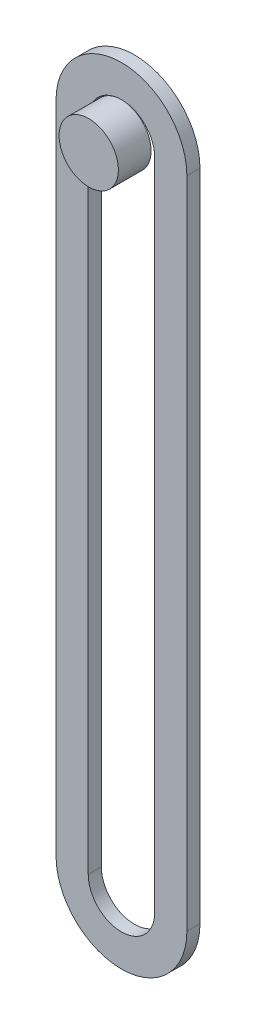
SolidWorks part; units mm, degrees
ref_plane "Front Plane" through (0, 0, 0) normal (0, 0, 1) x (1, 0, 0)
ref_plane "Top Plane" through (0, 0, 0) normal (0, 1, 0) x (1, 0, 0)
ref_plane "Right Plane" through (0, 0, 0) normal (1, 0, 0) x (0, 0, -1)
sketch "Sketch1" plane through (0, 0, 0) normal (0, 0, 1) x (1, 0, 0)
  line L0 (0, -56.0526) -> (0, 43.9474) construction
  line L1 (-10, -56.0526) -> (-10, 43.9474)
  line L2 (10, -56.0526) -> (10, 43.9474)
  line L3 (0, -56.0526) -> (0, 43.9474) construction
  line L4 (-5.0774, -56.0526) -> (-5.0774, 43.9474)
  line L5 (5.0774, -56.0526) -> (5.0774, 43.9474)
  arc A0 (-10, -56.0526) -> (10, -56.0526) centre (0, -56.0526) ccw
  arc A1 (10, 43.9474) -> (-10, 43.9474) centre (0, 43.9474) ccw
  arc A2 (-5.0774, -56.0526) -> (5.0774, -56.0526) centre (0, -56.0526) ccw
  arc A3 (5.0774, 43.9474) -> (-5.0774, 43.9474) centre (0, 43.9474) ccw
  point P3 (0, -6.0526)
  point P10 (0, -6.0526)
  dimension "D1" = 100
  dimension "D2" = 20
extrude "Boss-Extrude1" add sketch "Sketch1" along normal blind 2
sketch "Sketch2" plane through (0, 0, 2) normal (0, 0, 1) x (1, 0, 0)
  circle A0 centre (0, 44.4928) radius 4.532
extrude "Boss-Extrude2" add sketch "Sketch2" along normal blind 5 separate body
